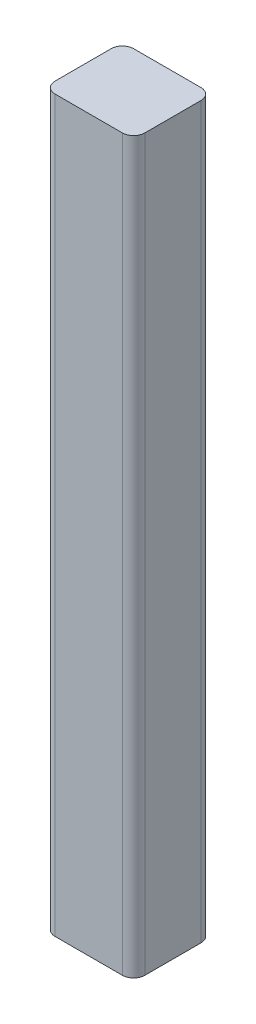
SolidWorks part; units mm, degrees
ref_plane "Front Plane" through (0, 0, 0) normal (0, 0, 1) x (1, 0, 0)
ref_plane "Top Plane" through (0, 0, 0) normal (0, 1, 0) x (1, 0, 0)
ref_plane "Right Plane" through (0, 0, 0) normal (1, 0, 0) x (0, 0, -1)
sketch "Sketch1" plane through (0, 0, 0) normal (0, 1, 0) x (1, 0, 0)
  line L0 (0, 0) -> (0, 2489.9286) construction
  line L1 (0, 0) -> (2489.9286, 0) construction
  line L3 (-4, -3.5) -> (4, -3.5)
  line L4 (-4, -3.5) -> (-4, 3.5)
  line L5 (-4, 3.5) -> (4, 3.5)
  line L6 (4, -3.5) -> (4, 3.5)
  line L7 (-4, -3.5) -> (4, 3.5) construction
  line L8 (-4, 3.5) -> (4, -3.5) construction
  point P5 (0, 0)
  dimension "D1" = 8
  dimension "D2" = 7
extrude "Boss-Extrude1" add sketch "Sketch1" along normal blind 65
fillet "Fillet1" radius 1 4 edges at (-4, 32.5, 3.5) (-4, 32.5, -3.5) (4, 32.5, -3.5) (4, 32.5, 3.5)
